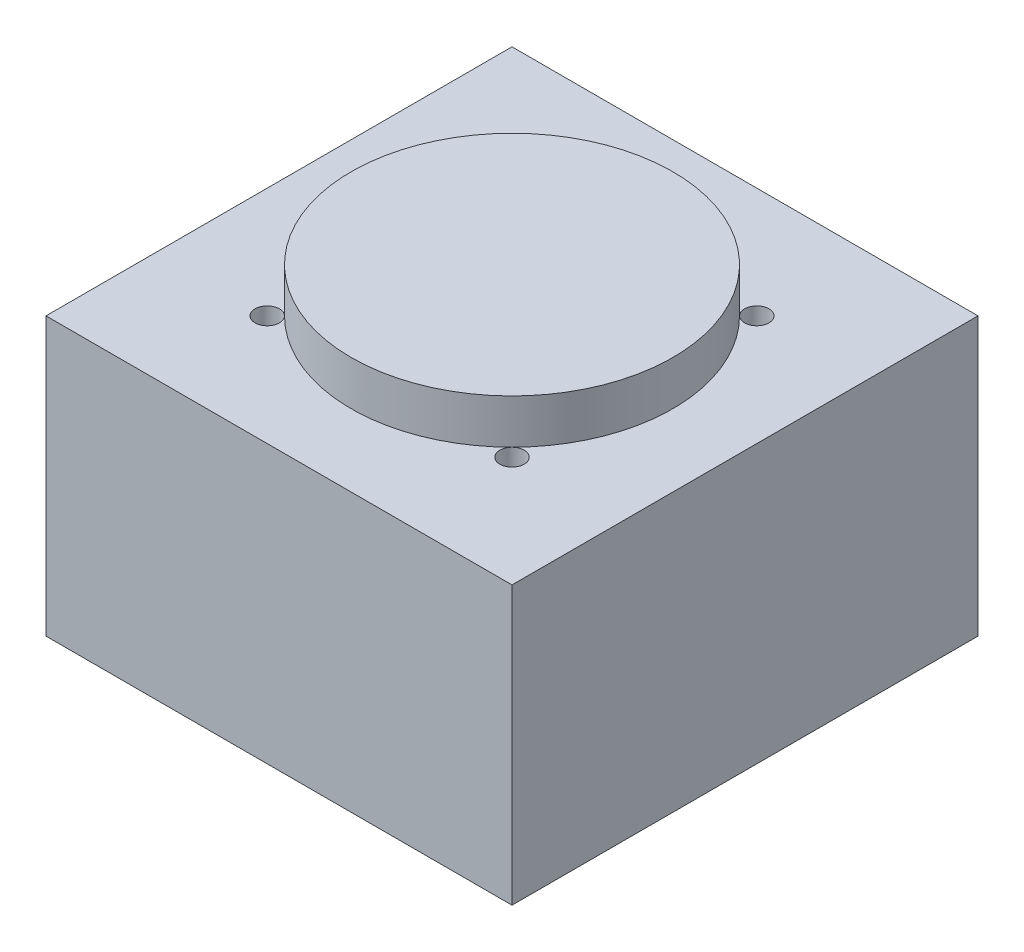
SolidWorks part; units mm, degrees
ref_plane "前视基准面" through (0, 0, 0) normal (0, 0, 1) x (1, 0, 0)
ref_plane "上视基准面" through (0, 0, 0) normal (0, 1, 0) x (1, 0, 0)
ref_plane "右视基准面" through (0, 0, 0) normal (1, 0, 0) x (0, 0, -1)
other "Configuration Table"
sketch "01_Housing_Profile" plane through (0, 0, 0) normal (0, 1, 0) x (1, 0, 0)
  line L1 (-105, -105) -> (105, -105)
  line L2 (-105, -105) -> (-105, 105)
  line L3 (-105, 105) -> (105, 105)
  line L4 (105, -105) -> (105, 105)
  line L5 (-105, -105) -> (105, 105) construction
  line L6 (-105, 105) -> (105, -105) construction
  circle A0 centre (55.1543, 55.1543) radius 5.5
  circle A1 centre (-55.1543, 55.1543) radius 5.5
  circle A2 centre (-55.1543, -55.1543) radius 5.5
  circle A3 centre (55.1543, -55.1543) radius 5.5
  point P0 (0, 0)
extrude "01_Housing_Block" add sketch "01_Housing_Profile" along normal blind 125
sketch "02_Face_Boss_Profile" plane through (0, 0, 0) normal (0, 1, 0) x (1, 0, 0)
  circle A0 centre (0, 0) radius 72.5
extrude "02_Face_Locating_Boss" add sketch "02_Face_Boss_Profile" along normal blind 145
